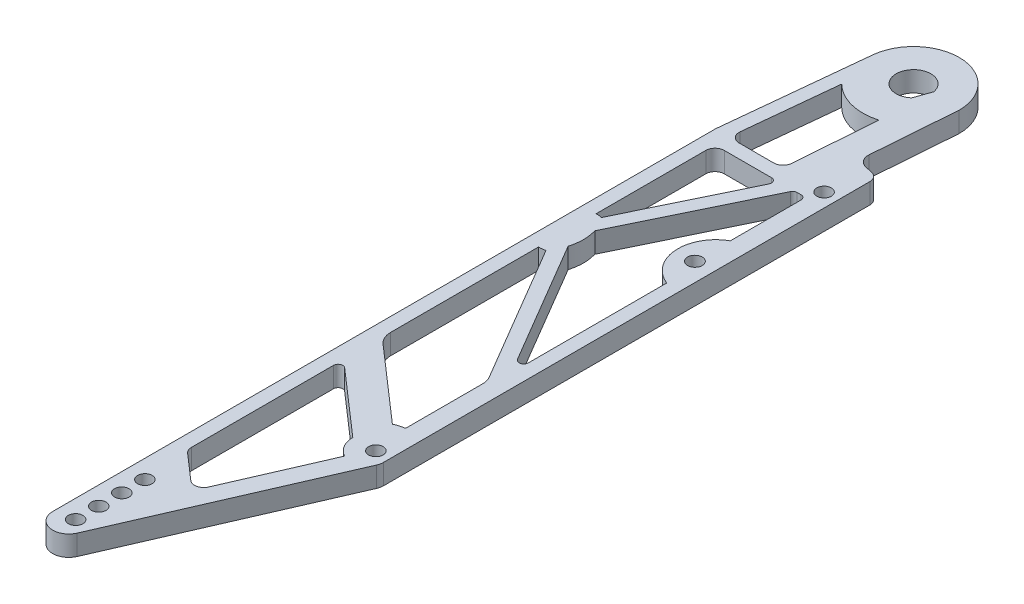
SolidWorks part; units mm, degrees
material "6061-T6 (SS)"
ref_plane "X-Y Datum" through (0, 0, 0) normal (0, 0, 1) x (1, 0, 0)
ref_plane "X-Z Datum" through (0, 0, 0) normal (0, 1, 0) x (1, 0, 0)
ref_plane "Y-Z Datum" through (0, 0, 0) normal (1, 0, 0) x (0, 0, -1)
other "Graphic1" [suppressed]
other "Graphic (Closed) -1" [suppressed]
sketch "Sketch2" plane through (0, 0, 0) normal (0, 1, 0) x (1, 0, 0)
  line L5 (13.4859, -161.3958) -> (-11.43, -139.6278) construction
  line L8 (0, 0) -> (0.7349, -24.1188) construction
  line L11 (15.3044, -26.8434) -> (13.2844, -26.3967)
  line L15 (-16.51, -220.3139) -> (-16.51, -38.0351)
  line L22 (-7.9887, -222.0863) -> (16.9799, -164.6625)
  line L23 (17.2959, -163.1433) -> (17.2959, -29.3235)
  line L33 (10.4385, -166.9668) -> (-0.894, -193.0299)
  line L44 (-8.8047, -78.8772) -> (8.7509, -42.6265)
  line L45 (9.8939, -41.91) -> (10.9459, -41.91)
  line L47 (11.153, -120.1131) -> (-8.8047, -86.2228)
  line L49 (-12.4132, -35.3011) -> (-9.8148, -9.9414)
  line L51 (3.8964, -13.4156) -> (2.1949, -35.7529)
  line L53 (-0.3377, -38.1) -> (-9.8864, -38.1)
  line L56 (2.8385, -41.91) -> (-10.16, -41.91)
  line L57 (13.97, -23.2966) -> (0, 0) construction
  line L58 (10.8042, -23.0554) -> (12.5603, 0)
  line L59 (-12.7, -146.862) -> (-12.7, -185.9568)
  line L63 (7.1359, -161.3958) -> (-10.5944, -145.9056)
  line L64 (-12.7, -74.6125) -> (-12.7, -44.45)
  line L65 (3.9815, -43.7335) -> (-11.056, -74.7846)
  line L66 (-16.4968, -37.7762) -> (-12.4949, 1.2803)
  line L67 (-4.8945, -193.9299) -> (-11.8311, -187.8696)
  line L68 (6.9813, -41.91) -> (-12.7, -82.55) construction
  line L69 (-1.1448, -63.0603) -> (-4.5739, -61.3997) construction
  line L70 (9.4184, -152.783) -> (-10.9623, -134.9772)
  line L71 (12.2159, -151.9558) -> (12.2159, -130.811)
  line L72 (11.5133, -128.2332) -> (-10.8443, -90.2675)
  line L75 (-12.7, -131.1516) -> (-12.7, -90.4875)
  line L76 (4.6927, 0.8838) -> (3.1117, -3.6221)
  line L77 (3.9022, -1.3692) -> (0, 0) construction
  line L78 (12.2159, -43.18) -> (12.2159, -62.6181)
  line L79 (13.5167, -81.4131) -> (13.5167, -119.4314)
  line L80 (0, 0) -> (-4.7752, 0) construction
  circle A0 centre (0, 0) radius 4.7752
  circle A2 centre (-11.43, -219.075) radius 2
  circle A3 centre (-11.43, -212.725) radius 2
  circle A4 centre (-11.43, -206.375) radius 2
  circle A5 centre (-11.43, -200.025) radius 2
  circle A7 centre (0, 0) radius 12.5603 construction
  circle A12 centre (13.4859, -38.1) radius 2
  arc A13 (-12.4949, 1.2803) -> (12.5603, 0) centre (0, 0) cw
  arc A14 (-8.8047, -86.2228) -> (-8.8047, -78.8772) centre (-20.962, -82.55) ccw
  circle A16 centre (24.0125, -12.7) radius 3.175 construction
  arc A17 (24.0125, -12.7) -> (13.97, -23.2966) centre (0, 0) cw construction
  circle A18 centre (13.97, -23.2966) radius 3.175 construction
  arc A19 (13.2844, -26.3967) -> (10.8042, -23.0554) centre (13.97, -23.2966) cw
  arc A20 (15.3044, -26.8434) -> (17.2959, -29.3235) centre (14.7559, -29.3235) cw
  circle A21 centre (13.4859, -161.3958) radius 2
  arc A24 (10.4385, -166.9668) -> (7.1359, -161.3958) centre (13.4859, -161.3958) cw
  arc A25 (-16.51, -220.3139) -> (-7.9887, -222.0863) centre (-12.065, -220.3139) ccw
  arc A26 (-12.7, -74.6125) -> (-11.056, -74.7846) centre (-12.7, -82.55) cw
  arc A28 (3.8964, -13.4156) -> (-9.8148, -9.9414) centre (0, 0) cw
  arc A31 (-10.16, -41.91) -> (-12.7, -44.45) centre (-10.16, -44.45) ccw
  arc A32 (-12.4132, -35.3011) -> (-9.8864, -38.1) centre (-9.8864, -35.56) ccw
  arc A33 (-0.3377, -38.1) -> (2.1949, -35.7529) centre (-0.3377, -35.56) ccw
  arc A36 (-12.7, -146.862) -> (-10.5944, -145.9056) centre (-11.43, -146.862) cw
  arc A37 (11.153, -120.1131) -> (13.5167, -119.4314) centre (12.2473, -119.4686) ccw
  arc A38 (8.7509, -42.6265) -> (9.8939, -41.91) centre (9.8939, -43.18) cw
  arc A39 (10.9459, -41.91) -> (12.2159, -43.18) centre (10.9459, -43.18) cw
  arc A40 (2.8385, -41.91) -> (3.9815, -43.7335) centre (2.8385, -43.18) cw
  arc A50 (17.2959, -163.1433) -> (16.9799, -164.6625) centre (13.4859, -163.1433) cw
  arc A52 (-16.4968, -37.7762) -> (-16.51, -38.0351) centre (-13.97, -38.0351) ccw
  arc A53 (-12.7, -185.9568) -> (-11.8311, -187.8696) centre (-10.16, -185.9568) ccw
  arc A54 (-4.8945, -193.9299) -> (-0.894, -193.0299) centre (-3.2233, -192.0171) ccw
  arc A55 (12.2159, -151.9558) -> (9.4184, -152.783) centre (13.4859, -161.3958) ccw
  arc A56 (-10.8443, -90.2675) -> (-12.7, -90.4875) centre (-12.7, -82.55) cw
  arc A57 (-12.7, -131.1516) -> (-10.9623, -134.9772) centre (-7.62, -131.1516) ccw
  arc A58 (11.5133, -128.2332) -> (12.2159, -130.811) centre (7.1359, -130.811) cw
  arc A59 (12.2159, -62.6181) -> (13.5167, -81.4131) centre (17.2959, -71.7091) ccw
  circle A60 centre (12.2159, -71.7091) radius 2.032
  point P30 (17.2959, -27.2838)
  point P44 (-2.8594, -62.23)
  point P45 (-2.2789, -196.215)
  point P75 (-4.7752, 0)
  point P88 (-12.7, -41.91)
  point P91 (-12.7, -38.1)
  point P104 (12.2159, -121.6534)
  point P107 (9.0979, -41.91)
  point P110 (13.3913, -41.91)
  point P120 (17.2959, -163.9358)
  dimension "D1" = 9.5504
  dimension "D6" = 4
  dimension "D5" = 25.1206
  dimension "D19" = 4
  dimension "D50" = 12.7
  dimension "D62" = 6.35
  dimension "D20" = 6.35
  dimension "D27" = 2.54
  dimension "D44" = 4
  dimension "D36" = 6.35
  dimension "D33" = 13.97
  dimension "D18" = 4.445
  dimension "D48" = 2.54
  dimension "D49" = 1.27
  dimension "D58" = 2.54
  dimension "D29" = 7.9375
  dimension "D31" = 3.81
  dimension "D41" = 2.54
  dimension "D54" = 9.525
  dimension "D55" = 7.9375
  dimension "D57" = 5.08
  dimension "D65" = 10.414
  dimension "D25" = 4.064
  dimension "D7" = 6.35
  dimension "D8" = 6.35
  dimension "D9" = 6.35
  dimension "D12" = 24.13
  dimension "D22" = 38.1
  dimension "D26" = 3.81
  dimension "D47" = 4.2935
  dimension "D51" = 8.262
  dimension "D56" = 3.81
  dimension "D21" = 136.652
  dimension "D43" = 200.025
  dimension "D10" = 5.08
  dimension "D28" = 38.1
  dimension "D60" = 24.0125
  dimension "D61" = 12.7
  dimension "D63" = 29.204
  dimension "D13" = 4.1084
  dimension "D17" = 13.97
  dimension "D24" = 3.81
  dimension "D30" = 2.54
  dimension "D46" = 7.62
  dimension "D11" = 5.08
  dimension "D23" = 13.4859
  dimension "D15" = 82.55
  dimension "D16" = 12.7
  dimension "D34" = 3.81
  dimension "D37" = 16.51
  dimension "D40" = 23.5
  dimension "D45" = 6.35
  dimension "D32" = 3.81
  dimension "D59" = 3.81
  dimension "D35" = 3.81
  dimension "D38" = 3.81
  dimension "D39" = 8.89
  dimension "D42" = 3.81
  dimension "D52" = 3.81
  dimension "D53" = 3.81
  dimension "D14" = 5.08
  dimension "D66" = 10.8409
  dimension "D67" = 5.08
  dimension "D64" = 4.7752
  dimension "D68" = 68.92
  dimension "D69" = 5.08
extrude "Boss-Extrude1" add sketch "Sketch2" along normal blind 5.588 contours L76 A0
sketch "Sketch6" plane through (-16.51, 0, 0) normal (-1, 0, 0) x (0, 0, 1)
  line L0 (182.2139, 5.588) -> (182.2139, 0)
  line L1 (220.3139, 0) -> (38.0351, 0) construction
  line L2 (220.3139, 5.588) -> (38.0351, 5.588) construction
  line L3 (220.3139, 5.588) -> (220.3139, 0) construction
  dimension "D1" = 38.1
split line "Split Line2"
sketch "Sketch7" plane through (0, 5.588, 0) normal (0, 1, 0) x (1, 0, 0)
  line L0 (17.2959, -163.1433) -> (17.2959, -29.3235) construction
  circle A0 centre (12.2159, -72.3621) radius 2.032
  dimension "D3" = 4.064
  dimension "D1" = 5.08
  dimension "D2" = 9.144
extrude "Cut-Extrude1" cut sketch "Sketch7" against normal up to surface (5.588 mm away) up to face at (-0.2638, 0, 126.3444)
equation "\"D68@Sketch2\"=55.00+13.92"
